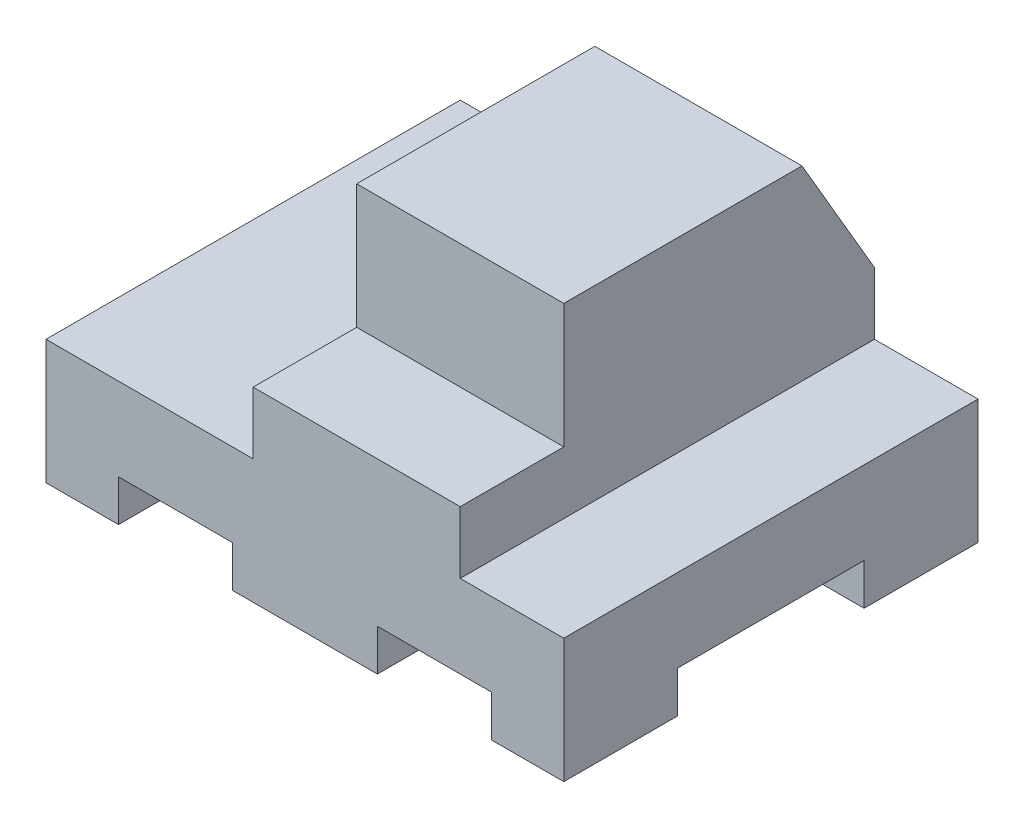
SolidWorks part; units mm, degrees
ref_plane "Спереди" through (0, 0, 0) normal (0, 0, 1) x (1, 0, 0)
ref_plane "Сверху" through (0, 0, 0) normal (0, 1, 0) x (1, 0, 0)
ref_plane "Справа" through (0, 0, 0) normal (1, 0, 0) x (0, 0, -1)
sketch "Эскиз1" plane through (0, 0, 0) normal (0, 0, 1) x (1, 0, 0)
  line L0 (-25, -3) -> (-5, -3)
  line L1 (-25, -15) -> (25, -15)
  line L2 (-25, -15) -> (-25, 15)
  line L3 (-25, 15) -> (25, 15)
  line L4 (25, -15) -> (25, 15)
  line L5 (-25, -15) -> (25, 15) construction
  line L6 (-25, 15) -> (25, -15) construction
  line L7 (-5, -3) -> (-5, 15)
  line L8 (15, 15) -> (15, -3)
  line L9 (15, -3) -> (25, -3)
  point P0 (0, 0)
  dimension "D1" = 50
  dimension "D2" = 30
  dimension "D3" = 12
  dimension "D4" = 20
  dimension "D5" = 10
extrude "Бобышка-Вытянуть1" add sketch "Эскиз1" along normal blind 40 contours L9 L8 L3 L7 L0 L2 L1 L4
sketch "Эскиз2" plane through (-25, 0, 0) normal (-1, 0, 0) x (0, 0, 1)
  line L0 (20, -3) -> (20, -15) construction
  line L1 (40, -3) -> (0, -3) construction
  line L2 (40, -15) -> (0, -15) construction
  line L4 (11, -15) -> (29, -15)
  line L5 (11, -15) -> (11, -11)
  line L6 (11, -11) -> (29, -11)
  line L7 (29, -15) -> (29, -11)
  line L8 (11, -15) -> (29, -11) construction
  line L9 (11, -11) -> (29, -15) construction
  point P6 (20, -13)
  dimension "D1" = 18
  dimension "D2" = 4
extrude "Вырез-Вытянуть1" cut sketch "Эскиз2" against normal through all
sketch "Эскиз3" plane through (0, 0, 40) normal (0, 0, 1) x (1, 0, 0)
  line L0 (0, -15) -> (0, 0) construction
  line L1 (-25, -15) -> (25, -15) construction
  line L2 (0, -15) -> (-25, -15) construction
  line L3 (-18, -15) -> (-7, -15)
  line L4 (-18, -15) -> (-18, -11)
  line L5 (-18, -11) -> (-7, -11)
  line L6 (-7, -15) -> (-7, -11)
  line L7 (-18, -15) -> (-7, -11) construction
  line L8 (-18, -11) -> (-7, -15) construction
  line L9 (-25, -15) -> (-25, -3) construction
  line L10 (-12.5, -15) -> (-12.5, -3) construction
  line L11 (-25, -15) -> (-25, -3)
  line L12 (-25, -3) -> (-5, -3) construction
  point P5 (-12.5, -13)
  line M7 (-25, -15) -> (25, -15)
  dimension "D1" = 11
  dimension "D2" = 4
extrude "Вырез-Вытянуть2" cut sketch "Эскиз3" against normal through all contours L6 L5 L4 M7
mirror "Зеркальное отражение1" about plane through (0, 0, 0) normal (1, 0, 0) of "Вырез-Вытянуть2"
sketch "Эскиз4" plane through (15, 0, 0) normal (1, 0, 0) x (0, 0, -1)
  line L0 (-7, 15) -> (0, 3)
  line L1 (-40, 15) -> (-30, 15)
  line L2 (-40, 15) -> (-40, 3)
  line L3 (-40, 3) -> (-30, 3)
  line L4 (-30, 15) -> (-30, 3)
  line L5 (-40, 15) -> (0, 15) construction
  line L6 (0, 15) -> (0, -3) construction
  line L7 (0, 3) -> (0, 15)
  line L8 (0, 15) -> (-7, 15)
  dimension "D1" = 10
  dimension "D2" = 12
  dimension "D3" = 7
extrude "Вырез-Вытянуть3" cut sketch "Эскиз4" against normal through all
